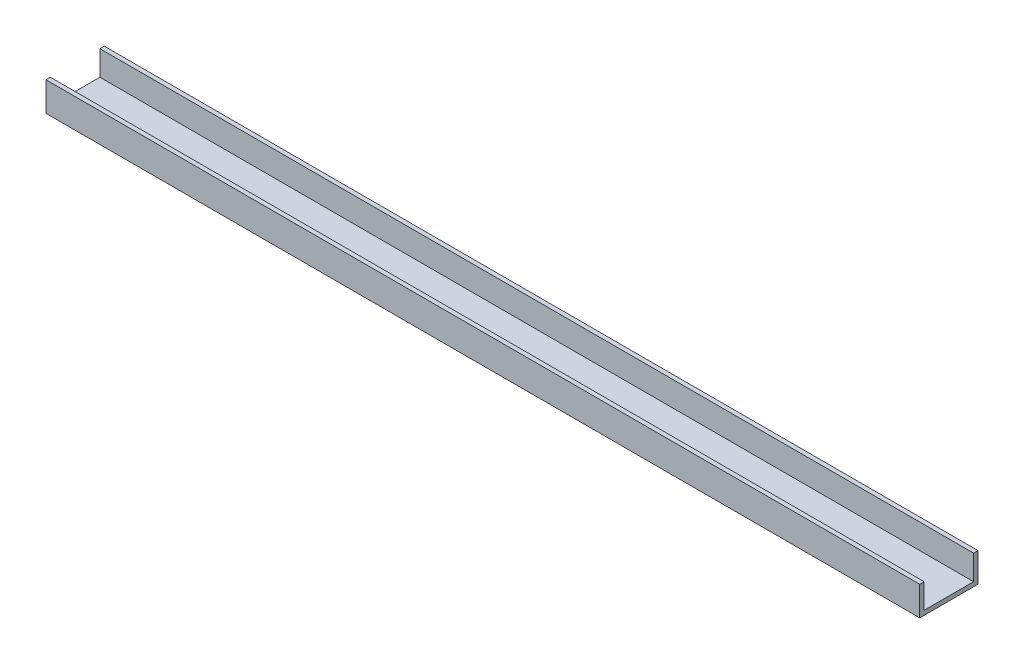
SolidWorks part; units mm, degrees
ref_plane "Front Plane" through (0, 0, 0) normal (0, 0, 1) x (1, 0, 0)
ref_plane "Top Plane" through (0, 0, 0) normal (0, 1, 0) x (1, 0, 0)
ref_plane "Right Plane" through (0, 0, 0) normal (1, 0, 0) x (0, 0, -1)
sketch "Sketch1" plane through (0, 0, 0) normal (1, 0, 0) x (0, 0, -1)
  line L0 (0, 43.9767) -> (0, -39.6063) construction
  line L1 (-83.9472, 0) -> (92.3237, 0) construction
  line L2 (-10, -6.4239) -> (10, -6.4239)
  line L3 (10, -6.4239) -> (10, 3.5761)
  line L4 (10, 3.5761) -> (8.5, 3.5761)
  line L5 (8.5, 3.5761) -> (8.5, -4.9239)
  line L6 (8.5, -4.9239) -> (-8.5, -4.9239)
  line L7 (-8.5, -4.9239) -> (-8.5, 3.5761)
  line L8 (-8.5, 3.5761) -> (-10, 3.5761)
  line L9 (-10, 3.5761) -> (-10, -6.4239)
  dimension "D1" = 20
  dimension "D2" = 1.5
  dimension "D3" = 1.5
  dimension "D4" = 1.5
  dimension "D5" = 10
extrude "Boss-Extrude1" add sketch "Sketch1" along normal blind 300
